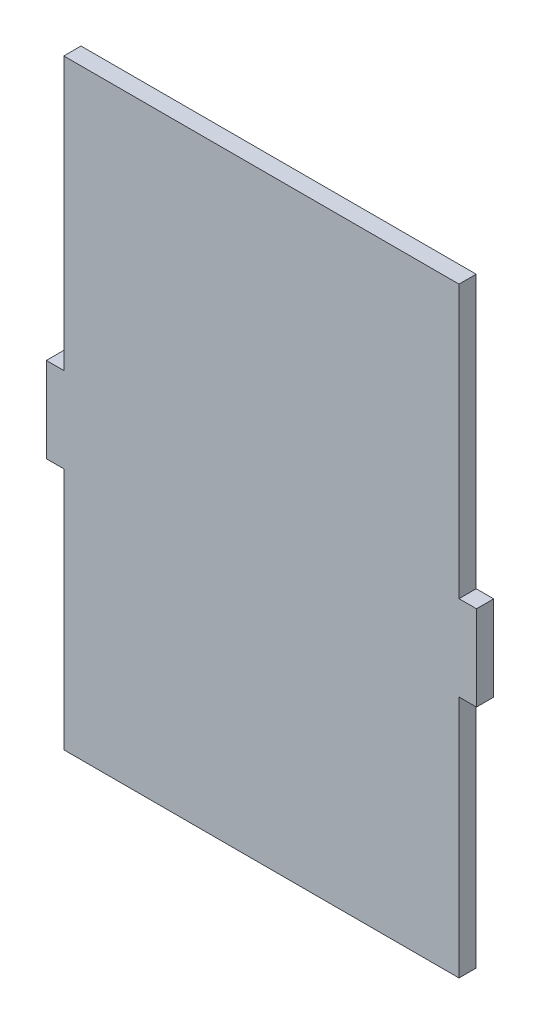
SolidWorks part; units mm, degrees
material "Плата обработки данных, простая"
ref_plane "Спереди" through (0, 0, 0) normal (0, 0, 1) x (1, 0, 0)
ref_plane "Сверху" through (0, 0, 0) normal (0, 1, 0) x (1, 0, 0)
ref_plane "Справа" through (0, 0, 0) normal (1, 0, 0) x (0, 0, -1)
sketch "Эскиз1" plane through (0, 0, 0) normal (0, 0, 1) x (1, 0, 0)
  line L0 (-22.987, 0) -> (-22.987, -51.689) construction
  line L1 (0, 0) -> (-45.974, 0)
  line L2 (0, 0) -> (0, -51.689)
  line L4 (-45.974, 0) -> (-45.974, -51.689)
  line L5 (-45.974, -51.689) -> (-48.006, -51.689)
  line L6 (0, -51.689) -> (2.032, -51.689)
  line L7 (-48.006, -51.689) -> (-48.006, -61.595)
  line L8 (-48.006, -61.595) -> (-45.974, -61.595)
  line L9 (2.032, -61.595) -> (2.032, -51.689)
  line L10 (0, 0) -> (0, -51.689)
  line L11 (0, -104.902) -> (-45.974, -104.902)
  line L12 (-45.974, -104.902) -> (-45.974, -61.595)
  line L13 (0, -61.595) -> (2.032, -61.595)
  line L14 (-22.987, -61.595) -> (-22.987, -84.0464) construction
  line L15 (0, -61.595) -> (0, -104.902)
  dimension "D1" = 45.974
  dimension "D2" = 51.689
  dimension "D3" = 2.032
  dimension "D4" = 2.032
  dimension "D5" = 9.906
  dimension "D6" = 104.902
extrude "Бобышка-Вытянуть1" add sketch "Эскиз1" along normal blind 2 contours L15 L13 L9 L6 L2 L1 L4 L5 L7 L8 L12 L11
sketch "Эскиз2" plane through (0, 0, 0) normal (0, 0, -1) x (-1, 0, 0)
  line L0 (0, 0) -> (0, -20)
  line L1 (0, 0) -> (0, -51.689) construction
  line L2 (0, -104.902) -> (0, -89.902)
  line L3 (0, -61.595) -> (0, -104.902) construction
  line L4 (0, 0) -> (45.974, 0)
  line L5 (45.974, 0) -> (45.974, -20)
  line L6 (45.974, 0) -> (45.974, -51.689) construction
  line L7 (45.974, -20) -> (0, -20)
  line L8 (0, -89.902) -> (45.974, -89.902)
  line L9 (45.974, -104.902) -> (45.974, -61.595) construction
  line L10 (45.974, -89.902) -> (45.974, -104.902)
  line L11 (45.974, -104.902) -> (0, -104.902)
  dimension "D1" = 20
  dimension "D2" = 15
extrude "Вырез-Вытянуть1" cut sketch "Эскиз2" against normal blind 10
